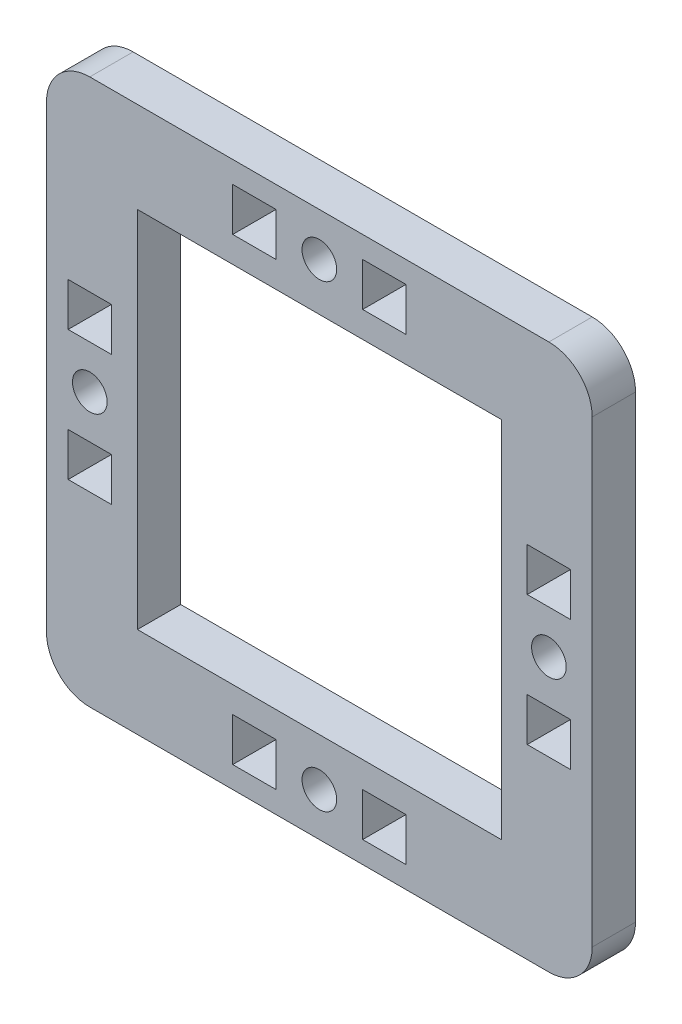
SolidWorks part; units mm, degrees
ref_plane "Plan de face" through (0, 0, 0) normal (0, 0, 1) x (1, 0, 0)
ref_plane "Plan de dessus" through (0, 0, 0) normal (0, 1, 0) x (1, 0, 0)
ref_plane "Plan de droite" through (0, 0, 0) normal (1, 0, 0) x (0, 0, -1)
sketch "Esquisse1" plane through (0, 0, 0) normal (0, 0, 1) x (1, 0, 0)
  line L0 (-24, 24) -> (24, 24) construction
  line L1 (24, 24) -> (24, -24) construction
  line L2 (24, -24) -> (-24, -24) construction
  line L3 (-24, -24) -> (-24, 24) construction
  line L4 (0, 0) -> (0, 24) construction
  line L5 (0, 0) -> (24, 0) construction
  line L6 (-21, 21) -> (21, 21)
  line L7 (21, 21) -> (21, -21)
  line L8 (21, -21) -> (-21, -21)
  line L9 (-21, -21) -> (-21, 21)
  line L10 (-31.5, 31.5) -> (31.5, 31.5)
  line L11 (31.5, 31.5) -> (31.5, -31.5)
  line L12 (31.5, -31.5) -> (-31.5, -31.5)
  line L13 (-31.5, -31.5) -> (-31.5, 31.5)
  line B0 (29, 5) -> (29, 10)
  line B1 (29, 5) -> (24, 5)
  line B2 (24, 5) -> (24, 10)
  line B3 (29, 10) -> (24, 10)
  line B4 (29, -5) -> (29, -10)
  line B5 (29, -5) -> (24, -5)
  line B6 (24, -5) -> (24, -10)
  line B7 (29, -10) -> (24, -10)
  line B8 (26.5, 0) -> (33.4724, 0) construction
  circle B9 centre (26.5, 0) radius 2
  line B10 (-29, 5) -> (-29, 10)
  line B11 (-29, 5) -> (-24, 5)
  line B12 (-24, 5) -> (-24, 10)
  line B13 (-29, 10) -> (-24, 10)
  line B14 (-29, -5) -> (-29, -10)
  line B15 (-29, -5) -> (-24, -5)
  line B16 (-24, -5) -> (-24, -10)
  line B17 (-29, -10) -> (-24, -10)
  circle B18 centre (-26.5, 0) radius 2
  line B19 (5, 29) -> (10, 29)
  line B20 (5, 29) -> (5, 24)
  line B21 (5, 24) -> (10, 24)
  line B22 (10, 29) -> (10, 24)
  line B23 (-5, 29) -> (-10, 29)
  line B24 (-5, 29) -> (-5, 24)
  line B25 (-5, 24) -> (-10, 24)
  line B26 (-10, 29) -> (-10, 24)
  line B27 (0, 26.5) -> (0, 33.4724) construction
  circle B28 centre (0, 26.5) radius 2
  line B29 (5, -29) -> (10, -29)
  line B30 (5, -29) -> (5, -24)
  line B31 (5, -24) -> (10, -24)
  line B32 (10, -29) -> (10, -24)
  line B33 (-5, -29) -> (-10, -29)
  line B34 (-5, -29) -> (-5, -24)
  line B35 (-5, -24) -> (-10, -24)
  line B36 (-10, -29) -> (-10, -24)
  circle B37 centre (0, -26.5) radius 2
  dimension "D1" = 48
  dimension "D2" = 180
  dimension "D3" = 2.5
  dimension "D4" = 63
  dimension "D5" = 63
  dimension "D6" = 3
  dimension "D7" = 42
  dimension "D8" = 42
sketch_block_instance "Trou M4 plots 5mm-1"
sketch_block "Trou M4 plots 5mm" parameters "D2"=4, "D1"=5, "D3"=5, "D4"=10
sketch_block_instance "Trou M4 plots 5mm-3"
sketch_block_instance "Trou M4 plots 5mm-4"
sketch_block_instance "Trou M4 plots 5mm-5"
extrude "Boss.-Extru.1" add sketch "Esquisse1" along normal blind 5
fillet "Congé1" radius 5 4 edges at (31.5, -31.5, 2.5) (-31.5, -31.5, 2.5) (-31.5, 31.5, 2.5) (31.5, 31.5, 2.5)
